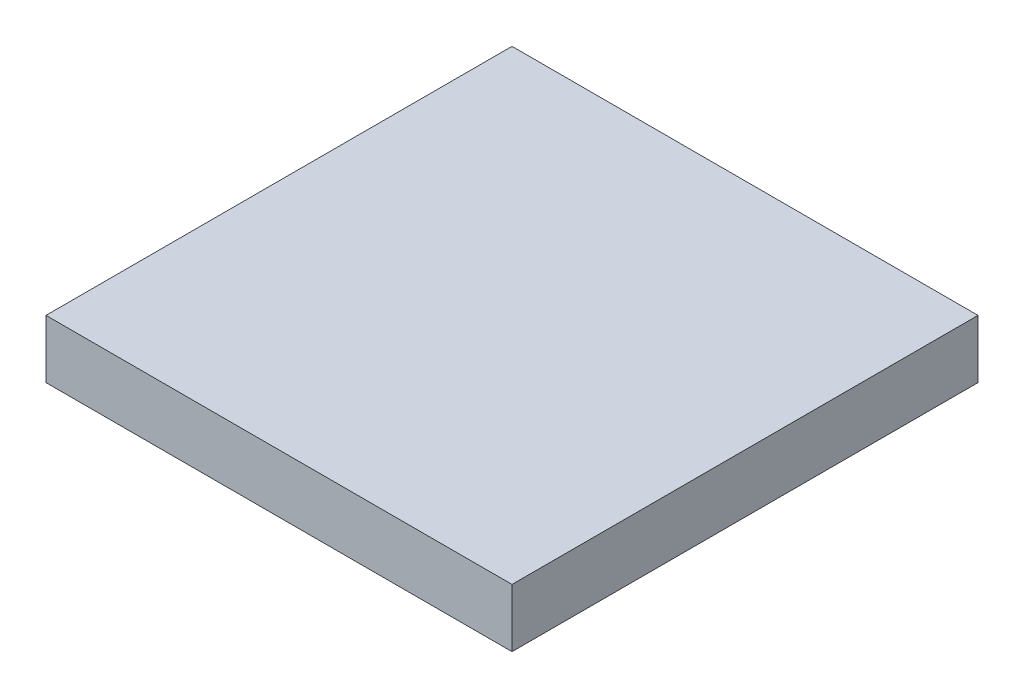
SolidWorks part; units mm, degrees
ref_plane "Front Plane" through (0, 0, 0) normal (0, 0, 1) x (1, 0, 0)
ref_plane "Top Plane" through (0, 0, 0) normal (0, 1, 0) x (1, 0, 0)
ref_plane "Right Plane" through (0, 0, 0) normal (1, 0, 0) x (0, 0, -1)
sketch "Sketch1" plane through (0, 0, 0) normal (0, 1, 0) x (1, 0, 0)
  line L1 (2, 2) -> (-2, 2)
  line L2 (2, 2) -> (2, -2)
  line L3 (2, -2) -> (-2, -2)
  line L4 (-2, 2) -> (-2, -2)
  line L5 (2, 2) -> (-2, -2) construction
  line L6 (2, -2) -> (-2, 2) construction
  point P0 (0, 0)
  dimension "D1" = 4
  dimension "D2" = 4
extrude "Boss-Extrude1" add sketch "Sketch1" along normal blind 0.5
